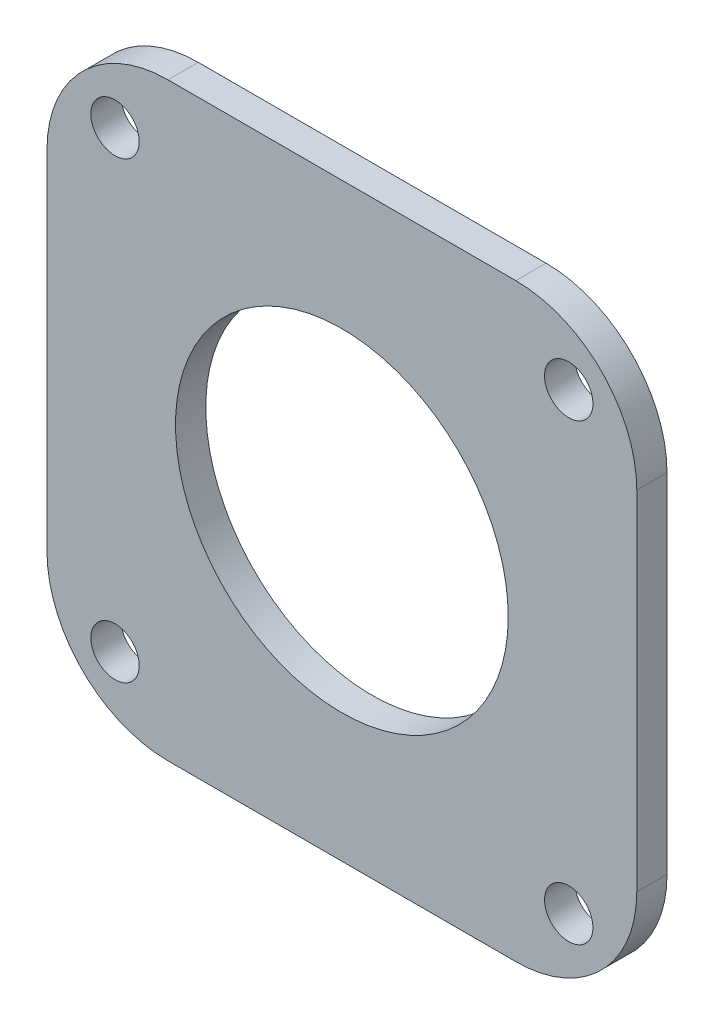
SolidWorks part; units mm, degrees
ref_plane "前视基准面" through (0, 0, 0) normal (0, 0, 1) x (1, 0, 0)
ref_plane "上视基准面" through (0, 0, 0) normal (0, 1, 0) x (1, 0, 0)
ref_plane "右视基准面" through (0, 0, 0) normal (1, 0, 0) x (0, 0, -1)
other "Configuration Table"
sketch "草图1" plane through (0, 0, 0) normal (0, 0, 1) x (1, 0, 0)
  line L1 (-20, -20) -> (20, -20)
  line L2 (-20, -20) -> (-20, 20)
  line L3 (-20, 20) -> (20, 20)
  line L4 (20, -20) -> (20, 20)
  line L5 (-20, -20) -> (20, 20) construction
  line L6 (-20, 20) -> (20, -20) construction
  line L7 (-20, 20) -> (-15, 20)
  line L8 (-20, 20) -> (-20, 15)
  line L9 (-20, 15) -> (-15, 15)
  line L10 (-15, 20) -> (-15, 15)
  line L11 (-19.5, -19.5) -> (19.5, -19.5)
  line L12 (-19.5, -19.5) -> (-19.5, 19.5)
  line L13 (-19.5, 19.5) -> (19.5, 19.5)
  line L14 (19.5, -19.5) -> (19.5, 19.5)
  line L15 (-19.5, -19.5) -> (19.5, 19.5) construction
  line L16 (-19.5, 19.5) -> (19.5, -19.5) construction
  circle A0 centre (0, 0) radius 5.5
  circle A1 centre (-15, 15) radius 1.6
  circle A2 centre (15, 15) radius 1.6
  circle A3 centre (15, -15) radius 1.6
  circle A4 centre (-15, -15) radius 1.6
  point P20 (0, 0)
  dimension "D1" = 11
  dimension "D5" = 3.2
  dimension "D2" = 40
  dimension "D3" = 40
  dimension "D4" = 5
  dimension "D7" = 39
  dimension "D6" = 4
extrude "凸台-拉伸2" add sketch "草图1" along normal blind 2 contours A1 L9 L12 L11 L14 L13 L10 A4 A3 A2 A0 | A1 L10 L13 L12 L9
fillet "圆角6" radius 8 1 edges at (-19.5, 19.5, 1)
fillet "圆角7" radius 8 1 edges at (19.5, 19.5, 1)
fillet "圆角8" radius 8 1 edges at (-19.5, -19.5, 1)
fillet "圆角9" radius 8 1 edges at (19.5, -19.5, 1)
sketch "草图2" plane through (0, 0, 2) normal (0, 0, 1) x (1, 0, 0)
  circle A0 centre (0, 0) radius 11
  dimension "D1" = 22
extrude "切除-拉伸1" cut sketch "草图2" against normal blind 10
